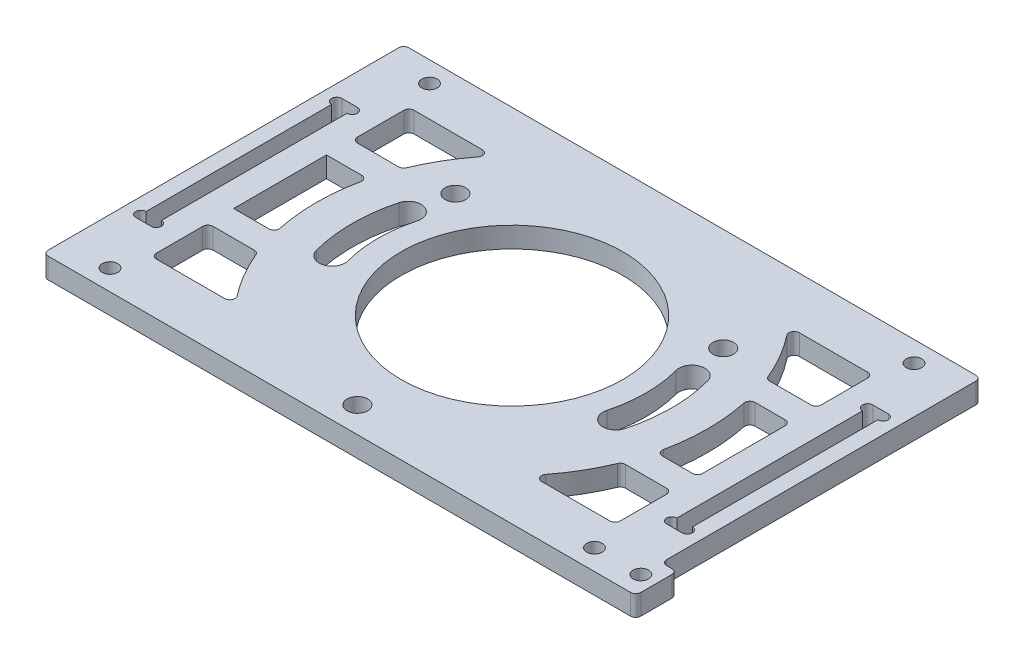
SolidWorks part; units mm, degrees
material "Thornel Mat VMA"
ref_plane "前视基准面" through (0, 0, 0) normal (0, 0, 1) x (1, 0, 0)
ref_plane "上视基准面" through (0, 0, 0) normal (0, 1, 0) x (1, 0, 0)
ref_plane "右视基准面" through (0, 0, 0) normal (1, 0, 0) x (0, 0, -1)
sketch "草图1" plane through (0, 0, 0) normal (0, 1, 0) x (1, 0, 0)
  line L0 (-56, 35) -> (56, 35)
  line L2 (-50, -20) -> (-50, 20)
  line L4 (50, -20) -> (50, 20)
  line L16 (-56, -35) -> (56, -35)
  line L20 (0, 0) -> (0, 39) construction
  line L21 (0, 0) -> (-56, 0) construction
  line L22 (-50, 20) -> (-53, 20)
  line L23 (-53, 20) -> (-53, -20)
  line L24 (-53, -20) -> (-50, -20)
  line L26 (0, -2.2) -> (0, 2.2) construction
  line L35 (53, -20) -> (50, -20)
  line L36 (53, 20) -> (53, -20)
  line L37 (50, 20) -> (53, 20)
  line L39 (-56, 35) -> (-56, -35)
  line L40 (56, 35) -> (56, -35)
  point P17 (-53, 0)
  dimension "D1" = 100
  dimension "D2" = 70
  dimension "D6" = 3
  dimension "D7" = 3
  dimension "D9" = 40
extrude "凸台-拉伸1" add sketch "草图1" along normal blind 4
sketch "草图6" plane through (0, 4, 0) normal (0, 1, 0) x (1, 0, 0)
  line L0 (0, -2.2) -> (0, 2.2) construction
  circle A1 centre (0, 0) radius 21.5
  arc A5 (-27.5289, -7.3763) -> (-27.5289, 7.3763) centre (0, 0) cw construction
  arc A6 (-29.9437, 8.0234) -> (-29.9437, -8.0234) centre (0, 0) ccw
  arc A7 (-25.1141, 6.7293) -> (-25.1141, -6.7293) centre (0, 0) ccw
  arc A8 (-25.1141, 6.7293) -> (-29.9437, 8.0234) centre (-27.5289, 7.3763) ccw
  arc A9 (-29.9437, -8.0234) -> (-25.1141, -6.7293) centre (-27.5289, -7.3763) ccw
  arc A15 (27.5289, -7.3763) -> (27.5289, 7.3763) centre (0, 0) ccw construction
  arc A46 (29.9437, 8.0234) -> (29.9437, -8.0234) centre (0, 0) cw
  arc A51 (25.1141, 6.7293) -> (25.1141, -6.7293) centre (0, 0) cw
  circle A57 centre (0, 0) radius 30 construction
  circle A58 centre (-25.9808, 15) radius 2
  circle A59 centre (25.9808, 15) radius 2
  circle A60 centre (0, -30) radius 2
  arc A62 (25.1141, 6.7293) -> (29.9437, 8.0234) centre (27.5289, 7.3763) cw
  arc A63 (29.9437, -8.0234) -> (25.1141, -6.7293) centre (27.5289, -7.3763) cw
  point P13 (-28.5, 0)
  point P19 (28.5, 0)
  dimension "D1" = 43
  dimension "D3" = 4.5
  dimension "D4" = 2.5
  dimension "D7" = 60
  dimension "D8" = 4
  dimension "D5" = 30
  dimension "D6" = 3
extrude "切除-拉伸5" cut sketch "草图6" against normal through all
sketch "草图2" plane through (0, 4, 0) normal (0, 1, 0) x (1, 0, 0)
  line L0 (0, -2.2) -> (0, 2.2) construction
  line L2 (-50, -20) -> (-50, 20) construction
  line L3 (-2.2, 0) -> (2.2, 0) construction
  line L4 (56, 35) -> (-56, 35) construction
  circle A11 centre (-47, 31) radius 1.5
  circle A16 centre (47, 31) radius 1.5
  circle A17 centre (47, -31) radius 1.5
  circle A18 centre (-47, -31) radius 1.5
  dimension "D2" = 3
  dimension "D3" = 3
  dimension "D1" = 4
extrude "切除-拉伸1" cut sketch "草图2" against normal blind 10
sketch "草图4" plane through (0, 4, 0) normal (0, -1, 0) x (1, 0, 0)
  line L2 (0, -2.2) -> (0, 2.2) construction
  line L10 (-50, 20) -> (-50, -20) construction
  line L11 (-50, 20) -> (-50, -20) construction
  line L12 (-53, -20) -> (-53, 20) construction
  circle A13 centre (-50, 19) radius 1
  circle A14 centre (-50, -19) radius 1
  circle A15 centre (50, -19) radius 1
  circle A16 centre (50, 19) radius 1
  circle A17 centre (-53, 19) radius 1
  circle A18 centre (-53, -19) radius 1
  circle A19 centre (53, -19) radius 1
  circle A20 centre (53, 19) radius 1
  dimension "D2" = 2
extrude "切除-拉伸3" cut sketch "草图4" along normal through all
sketch "草图7" plane through (0, 4, 0) normal (0, 1, 0) x (1, 0, 0)
  line L0 (-28.6182, 25) -> (-45, 25)
  line L1 (-45, 25) -> (-45, 14)
  line L2 (-45, 14) -> (-35.327, 14)
  line L3 (-36.9188, 9) -> (-45, 9)
  line L5 (-2.2, 0) -> (2.2, 0) construction
  line L7 (-45, 9) -> (-45, -9)
  line L11 (-36.9188, -9) -> (-45, -9)
  line L12 (-45, -14) -> (-35.327, -14)
  line L13 (-45, -25) -> (-45, -14)
  line L14 (-28.6182, -25) -> (-45, -25)
  line L16 (-50, -18) -> (-50, 18) construction
  line L20 (0, -2.2) -> (0, 2.2) construction
  line L21 (28.6182, -25) -> (45, -25)
  line L22 (45, -25) -> (45, -14)
  line L23 (45, -14) -> (35.327, -14)
  line L24 (36.9188, -9) -> (45, -9)
  line L29 (45, 9) -> (45, -9)
  line L30 (36.9188, 9) -> (45, 9)
  line L31 (45, 14) -> (35.327, 14)
  line L32 (45, 25) -> (45, 14)
  line L33 (28.6182, 25) -> (45, 25)
  line L34 (56, 35) -> (-56, 35) construction
  arc A0 (-28.6182, 25) -> (-35.327, 14) centre (0, 0) ccw
  arc A1 (-36.9188, 9) -> (-36.9188, -9) centre (0, 0) ccw
  arc A2 (-28.6182, -25) -> (-35.327, -14) centre (0, 0) cw
  arc A4 (28.6182, -25) -> (35.327, -14) centre (0, 0) ccw
  arc A5 (36.9188, 9) -> (36.9188, -9) centre (0, 0) cw
  arc A6 (28.6182, 25) -> (35.327, 14) centre (0, 0) cw
  dimension "D1" = 5
  dimension "D4" = 38
  dimension "D2" = 10
  dimension "D3" = 5
  dimension "D5" = 18
extrude "切除-拉伸6" cut sketch "草图7" against normal through all
sketch "草图8" plane through (0, 4, 0) normal (0, 1, 0) x (1, 0, 0)
  line L0 (53, -18) -> (53, 18) construction
  line L1 (56, -35) -> (59, -35)
  line L2 (56, -35) -> (56, -27)
  line L3 (56, -27) -> (59, -27)
  line L4 (59, -35) -> (59, -27)
  line L5 (56, -35) -> (56, 35) construction
  line L6 (-56, -35) -> (56, -35) construction
  line L7 (56, -31) -> (47, -31) construction
  circle A2 centre (56, -31) radius 1.5 construction
  circle A3 centre (47, -31) radius 1.5 construction
  dimension "D3" = 3
  dimension "D1" = 3
  dimension "D2" = 8
extrude "凸台-拉伸2" add sketch "草图8" against normal up to surface (4 mm away) up to face at (38.6037, 0, -19.5716)
sketch "草图9" plane through (0, 4, 0) normal (0, 1, 0) x (1, 0, 0)
  circle A0 centre (56, -31) radius 1.5 construction
  circle A1 centre (56, -31) radius 1.5
extrude "切除-拉伸7" cut sketch "草图9" against normal through all
fillet "圆角3" radius 1 28 edges at (-56, 2, 35) (56, 2, -35) (-56, 2, -35) (-45, 2, -14) (-45, 2, -25) (-28.6182, 2, -25) (-35.327, 2, -14) (45, 2, -9) (45, 2, 9) (36.9188, 2, 9) (36.9188, 2, -9) (45, 2, -25) (45, 2, -14) (35.327, 2, -14) (28.6182, 2, -25) (45, 2, 14) (45, 2, 25) (28.6182, 2, 25) (35.327, 2, 14) (-45, 2, 25) (-45, 2, 14) (-35.327, 2, 14) (-28.6182, 2, 25) (-36.9188, 2, -9) (-36.9188, 2, 9) (59, 2, 35) (59, 2, 27) (56, 2, 27)
